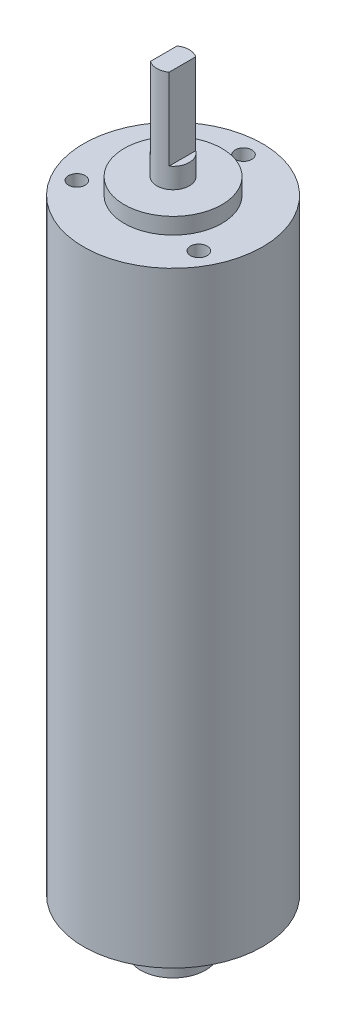
SolidWorks part; units mm, degrees
ref_plane "前视基准面" through (0, 0, 0) normal (0, 0, 1) x (1, 0, 0)
ref_plane "上视基准面" through (0, 0, 0) normal (0, 1, 0) x (1, 0, 0)
ref_plane "右视基准面" through (0, 0, 0) normal (1, 0, 0) x (0, 0, -1)
sketch "草图1" plane through (0, 0, 0) normal (0, 0, 1) x (1, 0, 0)
  line L0 (0, 0) -> (0, 95) construction
  line L1 (0, 0) -> (4, 0)
  line L2 (4, 0) -> (4, 3)
  line L3 (4, 3) -> (1.5, 3)
  line L4 (1.5, 3) -> (1.5, 6)
  line L5 (1.5, 6) -> (11, 6)
  line L6 (11, 6) -> (11, 80.5)
  line L7 (11, 80.5) -> (6, 80.5)
  line L8 (6, 80.5) -> (6, 82.5)
  line L9 (6, 82.5) -> (2, 82.5)
  line L10 (2, 82.5) -> (2, 95)
  line L11 (2, 95) -> (0, 95)
  line L12 (0, 95) -> (0, 0)
  dimension "D1" = 22
  dimension "D2" = 14.5
  dimension "D3" = 4
  dimension "D4" = 12
  dimension "D5" = 2
  dimension "D6" = 74.5
  dimension "D7" = 6
  dimension "D8" = 8
  dimension "D9" = 3
  dimension "D10" = 3
revolve "旋转1" add sketch "草图1" angle 360 about L0
sketch "草图2" plane through (0, 95, 0) normal (0, 1, 0) x (1, 0, 0)
  line L0 (-1.15, 1.6363) -> (-1.15, -1.6363)
  line L1 (1.15, 1.6363) -> (1.15, -1.6363)
  circle A1 centre (0, 0) radius 2
  circle A2 centre (0, 0) radius 2
  circle M4 centre (0, 0) radius 2
  dimension "D2" = 2.3
  dimension "D1" = 0
extrude "切除-拉伸1" cut sketch "草图2" against normal blind 10 contours L0 M4 | L1 M4
sketch "草图3" plane through (0, 80.5, 0) normal (0, 1, 0) x (1, 0, 0)
  circle A0 centre (0, 0) radius 8.6603 construction
  circle A1 centre (0, 8.6603) radius 1.25
  circle A2 centre (7.5, -4.3301) radius 1.25
  circle A3 centre (-7.5, -4.3301) radius 1.25
  point P11 (0, 0)
  dimension "D1" = 15
  dimension "D2" = 2.5
  dimension "D3" = 3
hole_wizard "M2.5 螺纹孔1" positions "草图4" profile "草图5" tap size "M2.5" standard "GB"
sketch "草图4" plane through (0, 80.5, 0) normal (0, 1, 0) x (1, 0, 0)
  point P0 (0, 8.6603)
  point P3 (-7.5, -4.3301)
  point P6 (7.5, -4.3301)
cosmetic thread "孔螺蚊线1" parameters "D1"=5, "D2"=2.5
cosmetic thread "孔螺蚊线2" parameters "D1"=5, "D2"=2.5
cosmetic thread "孔螺蚊线3" parameters "D1"=5, "D2"=2.5
sketch "草图5" plane through (0, 80.5, -8.6603) normal (1, 0, 0) x (0, 0, 1)
  line L0 (0, 0) -> (0, 6.9659)
  line L1 (0, 6.9659) -> (1.025, 6.35)
  line L2 (1.025, 6.35) -> (1.025, 0)
  line L5 (1.025, 0) -> (0, 0)
  line L10 (0, 6.9659) -> (-1.025, 6.35) construction
  line L11 (0, -6.35) -> (0, 107.95) construction
  dimension "螺纹孔钻头直径" = 2.05
  dimension "螺纹孔钻头深度" = 6.35
  dimension "导头角度" = 118
sketch "草图6" plane through (0, 6, 0) normal (0, -1, 0) x (1, 0, 0)
  line L0 (0, 0) -> (0, 4) construction
  circle A0 centre (-6.5, 0) radius 1
  circle A2 centre (6.5, 0) radius 1
  circle A3 centre (0, 0) radius 4 construction
  dimension "D2" = 2
  dimension "D1" = 13
hole_wizard "M2 螺纹孔1" positions "草图7" profile "草图8" tap size "M2" standard "GB"
sketch "草图7" plane through (0, 6, 0) normal (0, -1, 0) x (-1, 0, 0)
  point P0 (-6.5, 0)
  point P3 (6.5, 0)
sketch "草图8" plane through (6.5, 6, 0) normal (1, 0, 0) x (0, 0, -1)
  line L0 (0, 0) -> (0, 5.6807)
  line L1 (0, 5.6807) -> (0.8, 5.2)
  line L2 (0.8, 5.2) -> (0.8, 0)
  line L5 (0.8, 0) -> (0, 0)
  line L10 (0, 5.6807) -> (-0.8, 5.2) construction
  line L11 (0, -6.35) -> (0, 107.95) construction
  dimension "螺纹孔钻头直径" = 1.6
  dimension "螺纹孔钻头深度" = 5.2
  dimension "导头角度" = 118
cosmetic thread "孔螺蚊线4" parameters "D1"=4, "D2"=2
cosmetic thread "孔螺蚊线5" parameters "D1"=4, "D2"=2
